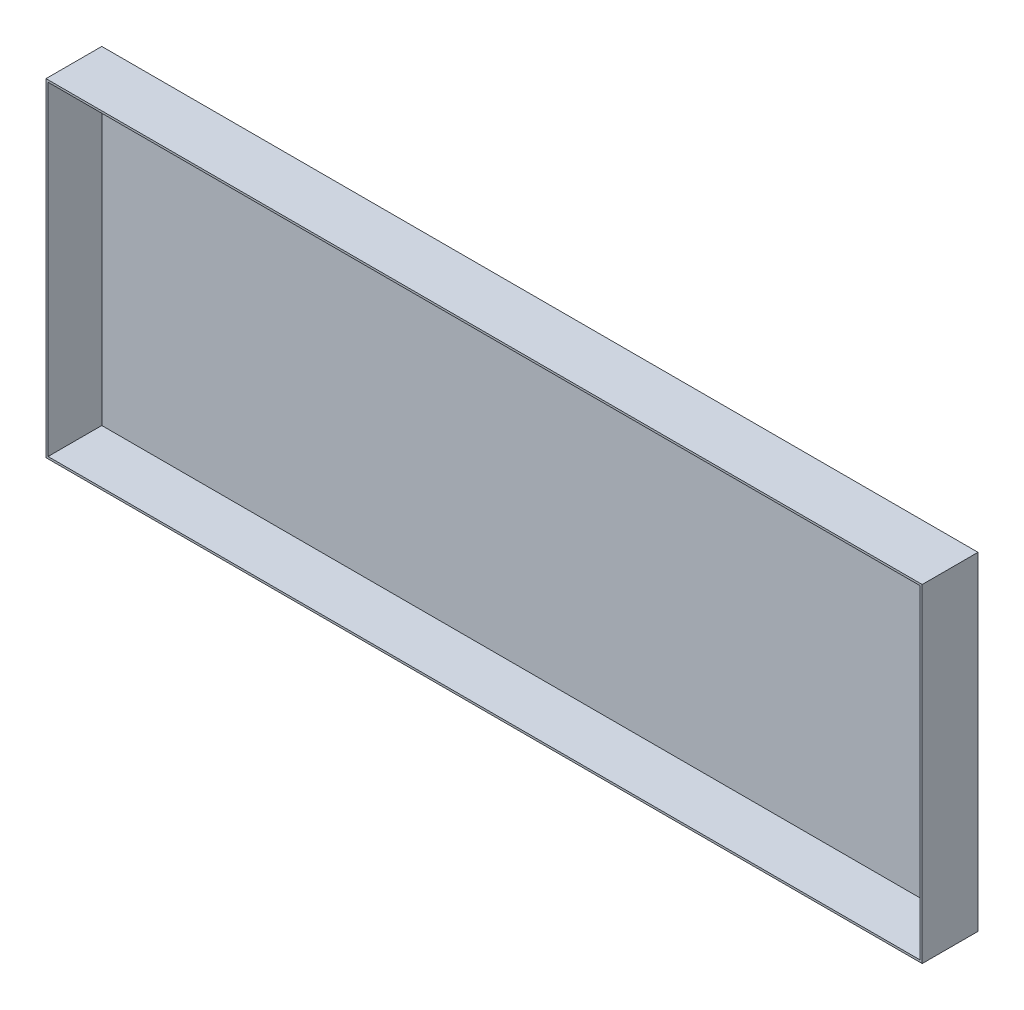
SolidWorks part; units mm, degrees
ref_plane "Alzado" through (0, 0, 0) normal (0, 0, 1) x (1, 0, 0)
ref_plane "Planta" through (0, 0, 0) normal (0, 1, 0) x (1, 0, 0)
ref_plane "Vista lateral" through (0, 0, 0) normal (1, 0, 0) x (0, 0, -1)
sketch "Croquis1" plane through (0, 0, 0) normal (0, 0, 1) x (1, 0, 0)
  line L1 (-399, 149.5) -> (399, 149.5)
  line L2 (-399, 149.5) -> (-399, -149.5)
  line L3 (-399, -149.5) -> (399, -149.5)
  line L4 (399, 149.5) -> (399, -149.5)
  line L5 (-399, 149.5) -> (399, -149.5) construction
  line L6 (-399, -149.5) -> (399, 149.5) construction
  point P0 (0, 0)
  dimension "D1" = 299
  dimension "D2" = 798
extrude "Saliente-Extruir1" add sketch "Croquis1" along normal blind 50.8
shell "Vaciado1" thickness 1.9
